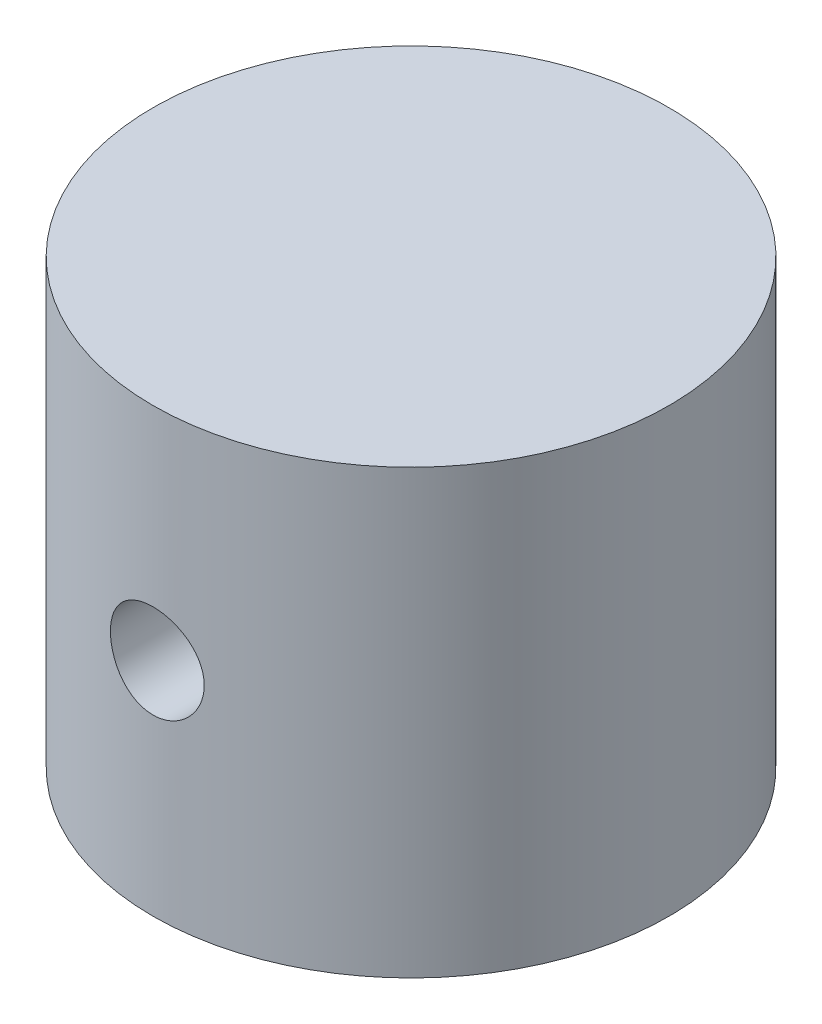
SolidWorks part; units mm, degrees
material "6061-T6 (SS)"
ref_plane "Front Plane" through (0, 0, 0) normal (0, 0, 1) x (1, 0, 0)
ref_plane "Top Plane" through (0, 0, 0) normal (0, 1, 0) x (1, 0, 0)
ref_plane "Right Plane" through (0, 0, 0) normal (1, 0, 0) x (0, 0, -1)
sketch "Sketch1" plane through (0, 0, 0) normal (0, 1, 0) x (1, 0, 0)
  circle A0 centre (0, 0) radius 11.1125
  dimension "D1" = 22.225
extrude "Boss-Extrude1" add sketch "Sketch1" along normal blind 19.05
hole_wizard "#10-32 Tapped Hole1" positions "3DSketch1" profile "Sketch3" tap size "#10-32" standard "ANSI Inch"
sketch3d "3DSketch1"
  line L0 (0, 0, 0) -> (0, 0, 11.1125) construction
  line L2 (0, 0, 11.1125) -> (0, 19.05, 11.1125) construction
  circle A0 centre (0, 0, 0) radius 11.1125 construction
  circle A1 centre (0, 19.05, 0) radius 11.1125 construction
  point P0 (0, 9.525, 11.1125)
  point P12 (0, 11.1125, 0)
  point P18 (0, 30.1625, 0)
sketch "Sketch3" plane through (0, 9.525, 11.1125) normal (1, 0, 0) x (0, -1, 0)
  line L0 (0, 0) -> (0, 12.3893)
  line L1 (0, 12.3893) -> (2.0193, 11.176)
  line L2 (2.0193, 11.176) -> (2.0193, 0)
  line L5 (2.0193, 0) -> (0, 0)
  line L10 (0, 12.3893) -> (-2.0193, 11.176) construction
  line L11 (0, -6.35) -> (0, 107.95) construction
  dimension "Tap Drill Dia." = 4.0386
  dimension "Tap Drill Depth" = 11.176
  dimension "Drill Angle" = 118
cosmetic thread "Hole Thread1" parameters "D1"=11.176, "D2"=4.826
